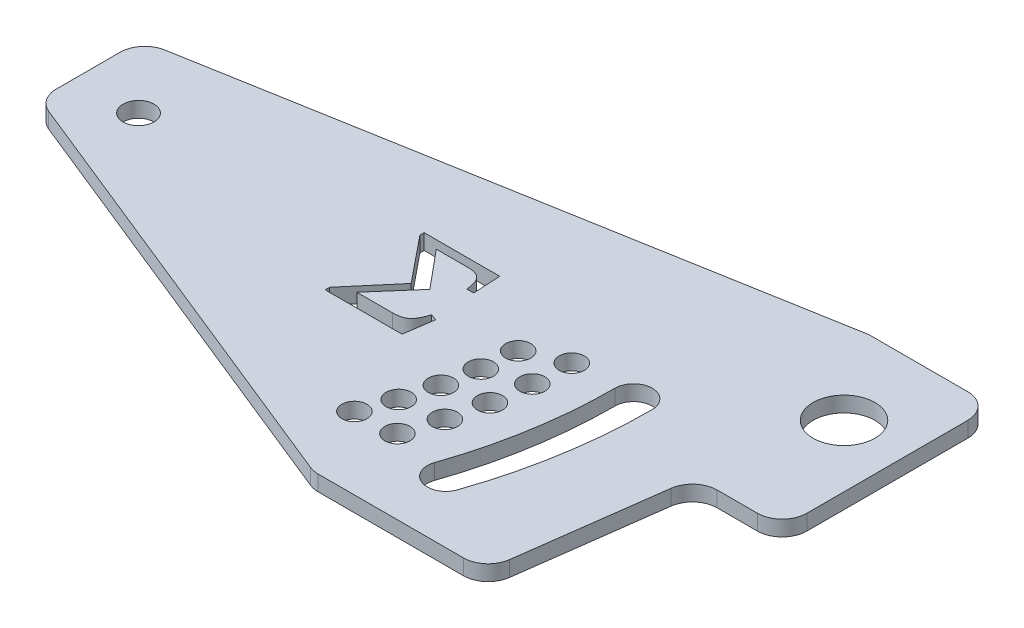
SolidWorks part; units mm, degrees
material "1060 Alloy"
ref_plane "Front Plane" through (0, 0, 0) normal (0, 0, 1) x (1, 0, 0)
ref_plane "Top Plane" through (0, 0, 0) normal (0, 1, 0) x (1, 0, 0)
ref_plane "Right Plane" through (0, 0, 0) normal (1, 0, 0) x (0, 0, -1)
sketch "Sketch1" plane through (0, 0, 0) normal (0, 1, 0) x (1, 0, 0)
  line L1 (0, 0) -> (152.4, 0)
  line L2 (0, 0) -> (0, 81.28)
  line L3 (0, 81.28) -> (152.4, 81.28)
  line L4 (152.4, 0) -> (152.4, 81.28)
  dimension "D1" = 81.28
  dimension "D2" = 152.4
extrude "Boss-Extrude1" add sketch "Sketch1" along normal blind 3.175
sketch "Sketch2" plane through (0, 3.175, 0) normal (0, 1, 0) x (1, 0, 0)
  line L0 (12.7, 45.72) -> (114.3, 45.72) construction
  line L1 (12.7, 45.72) -> (108.7845, 12.7) construction
  line L2 (0, 0) -> (152.4, 0) construction
  line L3 (0, 81.28) -> (0, 0) construction
  circle A0 centre (12.7, 45.72) radius 3.175
  arc A1 (118.11, 45.72) -> (110.49, 45.72) centre (114.3, 45.72) ccw
  arc A2 (105.1814, 13.9383) -> (112.3877, 11.4618) centre (108.7845, 12.7) ccw
  arc A3 (108.7845, 12.7) -> (114.3, 45.72) centre (12.7, 45.72) ccw construction
  circle A4 centre (139.7, 63.5) radius 6.35
  arc A5 (112.3877, 11.4618) -> (118.11, 45.72) centre (12.7, 45.72) ccw
  arc A6 (105.1814, 13.9383) -> (110.49, 45.72) centre (12.7, 45.72) ccw
  dimension "D1" = 33.02
  dimension "D2" = 6.35
  dimension "D3" = 7.62
  dimension "D5" = 12.7
  dimension "D4" = 101.6
  dimension "D6" = 45.72
  dimension "D7" = 12.7
  dimension "D8" = 127
  dimension "D9" = 17.78
extrude "Cut-Extrude1" cut sketch "Sketch2" against normal through all
chamfer "Chamfer1" distance 38.1 angle 68 1 edges at (0, 1.5875, 0)
chamfer "Chamfer2" distance 127 angle 10 1 edges at (0, 1.5875, -81.28)
sketch "Sketch3" plane through (0, 3.175, 0) normal (0, 1, 0) x (1, 0, 0)
  line L0 (134.62, 38.1) -> (129.54, 0)
  line L1 (129.54, 0) -> (152.4, 0)
  line L2 (152.4, 0) -> (152.4, 38.1)
  line L3 (152.4, 38.1) -> (134.62, 38.1)
  line L5 (94.3008, 0) -> (152.4, 0) construction
  dimension "D1" = 38.1
  dimension "D2" = 22.86
  dimension "D3" = 17.78
extrude "Cut-Extrude2" cut sketch "Sketch3" against normal through all
fillet "Fillet1" radius 5.08 8 edges at (0, 1.5875, -58.8865) (0, 1.5875, -38.1) (94.3008, 1.5875, 0) (129.54, 1.5875, 0) (134.62, 1.5875, -38.1) (127, 1.5875, -81.28) (152.4, 1.5875, -38.1) (152.4, 1.5875, -81.28)
sketch "Sketch4" plane through (0, 3.175, 0) normal (0, 1, 0) x (1, 0, 0)
  text T0 "S" font "Symbol" height 20.32
extrude "Cut-Extrude3" cut sketch "Sketch4" against normal through all
sketch "Sketch5" plane through (0, 3.175, 0) normal (0, 1, 0) x (1, 0, 0)
  line L0 (12.7, 45.72) -> (158.3431, 45.72) construction
  circle A0 centre (101.6, 45.72) radius 2.5797
  circle A1 centre (93.9129, 42.418) radius 2.5797
  dimension "D1" = 5.1594
  dimension "D4" = 3.302
  dimension "D2" = 88.9
  dimension "D3" = 81.28
extrude "Cut-Extrude4" cut sketch "Sketch5" against normal through all
pattern_circular "CirPattern1" count 5 over 20 about axis through (12.7, 0, -45.72) along (0, 1, 0) of "Cut-Extrude4"
